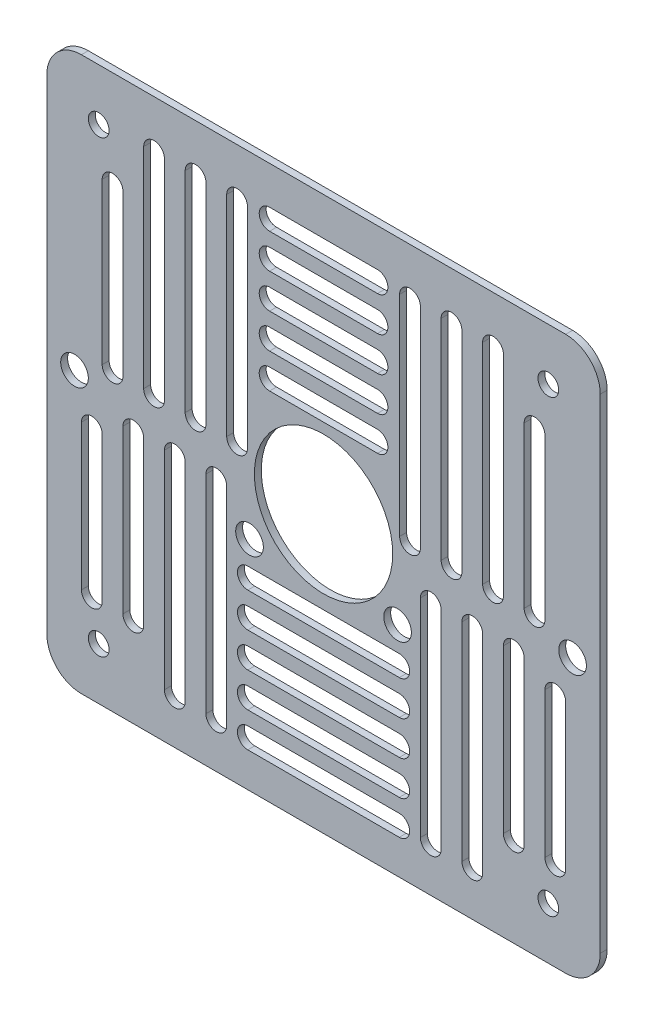
SolidWorks part; units mm, degrees
material "Fibra de vidrio-A"
ref_plane "Alzado" through (0, 0, 0) normal (0, 0, 1) x (1, 0, 0)
ref_plane "Planta" through (0, 0, 0) normal (0, 1, 0) x (1, 0, 0)
ref_plane "Vista lateral" through (0, 0, 0) normal (1, 0, 0) x (0, 0, -1)
sketch "Croquis1" plane through (0, 0, 0) normal (0, 0, 1) x (1, 0, 0)
  line L1 (-35, -40) -> (35, -40)
  line L2 (-40, -35) -> (-40, 35)
  line L3 (-35, 40) -> (35, 40)
  line L4 (40, -35) -> (40, 35)
  line L5 (-40, -40) -> (40, 40) construction
  line L6 (-40, 40) -> (40, -40) construction
  circle A0 centre (0, 0) radius 10
  arc A1 (35, -40) -> (40, -35) centre (35, -35) ccw
  arc A2 (-35, -40) -> (-40, -35) centre (-35, -35) cw
  arc A3 (35, 40) -> (40, 35) centre (35, 35) cw
  arc A4 (-40, 35) -> (-35, 40) centre (-35, 35) cw
  point P0 (0, 0)
  dimension "D2" = 20
  dimension "D3" = 5
  dimension "D1" = 80
extrude "Saliente-Extruir1" add sketch "Croquis1" against normal blind 1
sketch "Croquis2" plane through (0, 0, 0) normal (0, 0, 1) x (1, 0, 0)
  line L0 (-40, 0) -> (40, 0) construction
  line L1 (40, -35) -> (40, 35) construction
  line L2 (0, 0) -> (0, 10) construction
  line L3 (-35, -40) -> (35, -40) construction
  circle A0 centre (36, 0) radius 2
  circle A1 centre (0, 0) radius 10 construction
  circle A2 centre (-36, 0) radius 2
  circle A3 centre (32.5, -32.5) radius 1.5
  circle A4 centre (32.5, 32.5) radius 1.5
  circle A5 centre (-32.5, -32.5) radius 1.5
  circle A6 centre (-32.5, 32.5) radius 1.5
  circle A7 centre (10.7, -8.5) radius 2
  circle A8 centre (-10.7, -8.5) radius 2
  point P7 (0, 0)
  dimension "D1" = 4
  dimension "D2" = 4
  dimension "D3" = 3
  dimension "D4" = 7.5
  dimension "D6" = 4
  dimension "D7" = 31.5
  dimension "D8" = 29.3
  dimension "D5" = 7.5
extrude "Cortar-Extruir1" cut sketch "Croquis2" against normal blind 1
sketch "Croquis3" plane through (0, 0, 0) normal (0, 0, 1) x (1, 0, 0)
  line L0 (0, 0) -> (0, 40) construction
  line L1 (35, 40) -> (-35, 40) construction
  line L2 (-7.8, 33) -> (7.8, 33) construction
  line L3 (-7.8, 26.5) -> (7.8, 26.5)
  line L4 (-7.8, 34.5) -> (7.8, 34.5)
  line L5 (-7.8, 31.5) -> (7.8, 31.5)
  line L6 (-7.8, 29.5) -> (7.8, 29.5)
  line L7 (-7.8, 28) -> (7.8, 28) construction
  line L8 (-7.8, 21.5) -> (7.8, 21.5)
  line L9 (-7.8, 24.5) -> (7.8, 24.5)
  line L10 (-7.8, 23) -> (7.8, 23) construction
  line L11 (-7.8, 16.5) -> (7.8, 16.5)
  line L12 (-7.8, 19.5) -> (7.8, 19.5)
  line L13 (-7.8, 18) -> (7.8, 18) construction
  line L14 (-7.8, 11.5) -> (7.8, 11.5)
  line L15 (-7.8, 14.5) -> (7.8, 14.5)
  line L16 (-7.8, 13) -> (7.8, 13) construction
  line L17 (0, 0) -> (0, -40) construction
  line L18 (-35, -40) -> (35, -40) construction
  line L19 (-10.95, -33.5) -> (10.95, -33.5) construction
  line L20 (-10.95, -30) -> (10.95, -30)
  line L21 (-10.95, -32) -> (10.95, -32)
  line L22 (-10.95, -35) -> (10.95, -35)
  line L23 (-10.95, -27) -> (10.95, -27)
  line L24 (-10.95, -28.5) -> (10.95, -28.5) construction
  line L25 (-10.95, -25) -> (10.95, -25)
  line L26 (-10.95, -22) -> (10.95, -22)
  line L27 (-10.95, -23.5) -> (10.95, -23.5) construction
  line L28 (-10.95, -20) -> (10.95, -20)
  line L29 (-10.95, -17) -> (10.95, -17)
  line L30 (-10.95, -18.5) -> (10.95, -18.5) construction
  line L31 (-10.95, -15) -> (10.95, -15)
  line L32 (-10.95, -12) -> (10.95, -12)
  line L33 (-10.95, -13.5) -> (10.95, -13.5) construction
  arc A0 (-7.8, 34.5) -> (-7.8, 31.5) centre (-7.8, 33) ccw
  arc A1 (7.8, 31.5) -> (7.8, 34.5) centre (7.8, 33) ccw
  arc A2 (-7.8, 29.5) -> (-7.8, 26.5) centre (-7.8, 28) ccw
  arc A3 (7.8, 26.5) -> (7.8, 29.5) centre (7.8, 28) ccw
  arc A4 (-7.8, 24.5) -> (-7.8, 21.5) centre (-7.8, 23) ccw
  arc A5 (7.8, 21.5) -> (7.8, 24.5) centre (7.8, 23) ccw
  arc A6 (-7.8, 19.5) -> (-7.8, 16.5) centre (-7.8, 18) ccw
  arc A7 (7.8, 16.5) -> (7.8, 19.5) centre (7.8, 18) ccw
  arc A8 (-7.8, 14.5) -> (-7.8, 11.5) centre (-7.8, 13) ccw
  arc A9 (7.8, 11.5) -> (7.8, 14.5) centre (7.8, 13) ccw
  arc A10 (-10.95, -32) -> (-10.95, -35) centre (-10.95, -33.5) ccw
  arc A11 (10.95, -35) -> (10.95, -32) centre (10.95, -33.5) ccw
  arc A12 (-10.95, -27) -> (-10.95, -30) centre (-10.95, -28.5) ccw
  arc A13 (10.95, -30) -> (10.95, -27) centre (10.95, -28.5) ccw
  arc A14 (-10.95, -22) -> (-10.95, -25) centre (-10.95, -23.5) ccw
  arc A15 (10.95, -25) -> (10.95, -22) centre (10.95, -23.5) ccw
  arc A16 (-10.95, -17) -> (-10.95, -20) centre (-10.95, -18.5) ccw
  arc A17 (10.95, -20) -> (10.95, -17) centre (10.95, -18.5) ccw
  arc A18 (-10.95, -12) -> (-10.95, -15) centre (-10.95, -13.5) ccw
  arc A19 (10.95, -15) -> (10.95, -12) centre (10.95, -13.5) ccw
  point P9 (0, 33)
  point P15 (0, 28)
  point P22 (0, 23)
  point P29 (0, 18)
  point P36 (0, 13)
  point P47 (0, -33.5)
  point P54 (0, -28.5)
  point P61 (0, -23.5)
  point P68 (0, -18.5)
  point P75 (0, -13.5)
  dimension "D3" = 5
  dimension "D1" = 5.5
  dimension "D2" = 3
  dimension "D4" = 3
  dimension "D5" = 5
  dimension "D7" = 21.9
  dimension "D8" = 15.6
  dimension "D6" = 5
extrude "Cortar-Extruir2" cut sketch "Croquis3" against normal blind 1
sketch "Croquis4" plane through (0, 0, 0) normal (0, 0, 1) x (1, 0, 0)
  line L0 (12.5, 2.7) -> (12.5, 33) construction
  line L1 (40, -35) -> (40, 35) construction
  line L2 (11, 2.7) -> (11, 33)
  line L3 (14, 2.7) -> (14, 33)
  line L4 (3.8705, 34.5) -> (26.7887, 34.5) construction
  line L5 (18.5, 2.7) -> (18.5, 33) construction
  line L6 (7.8, 34.5) -> (-7.8, 34.5) construction
  line L7 (17, 2.7) -> (17, 33)
  line L8 (20, 2.7) -> (20, 33)
  line L9 (24.5, 2.7) -> (24.5, 33) construction
  line L10 (23, 2.7) -> (23, 33)
  line L11 (26, 2.7) -> (26, 33)
  line L12 (12.5, 1.2) -> (40, 1.2) construction
  line L13 (30.5, 25.9) -> (30.5, 2.7) construction
  line L14 (0, 0) -> (0, 40) construction
  line L15 (32, 25.9) -> (32, 2.7)
  line L16 (29, 25.9) -> (29, 2.7)
  line L17 (35, 40) -> (-35, 40) construction
  line L18 (-12.5, 2.7) -> (-12.5, 33) construction
  line L19 (-11, 2.7) -> (-11, 33)
  line L20 (-14, 2.7) -> (-14, 33)
  line L21 (-18.5, 2.7) -> (-18.5, 33) construction
  line L22 (-17, 2.7) -> (-17, 33)
  line L23 (-20, 2.7) -> (-20, 33)
  line L24 (-24.5, 2.7) -> (-24.5, 33) construction
  line L25 (-23, 2.7) -> (-23, 33)
  line L26 (-26, 2.7) -> (-26, 33)
  line L27 (-30.5, 25.9) -> (-30.5, 2.7) construction
  line L28 (-32, 25.9) -> (-32, 2.7)
  line L29 (-29, 25.9) -> (-29, 2.7)
  arc A0 (11, 2.7) -> (14, 2.7) centre (12.5, 2.7) ccw
  arc A1 (14, 33) -> (11, 33) centre (12.5, 33) ccw
  arc A2 (17, 2.7) -> (20, 2.7) centre (18.5, 2.7) ccw
  arc A3 (20, 33) -> (17, 33) centre (18.5, 33) ccw
  arc A4 (23, 2.7) -> (26, 2.7) centre (24.5, 2.7) ccw
  arc A5 (26, 33) -> (23, 33) centre (24.5, 33) ccw
  arc A6 (32, 25.9) -> (29, 25.9) centre (30.5, 25.9) ccw
  arc A7 (29, 2.7) -> (32, 2.7) centre (30.5, 2.7) ccw
  arc A8 (-11, 2.7) -> (-14, 2.7) centre (-12.5, 2.7) cw
  arc A9 (-14, 33) -> (-11, 33) centre (-12.5, 33) cw
  arc A10 (-17, 2.7) -> (-20, 2.7) centre (-18.5, 2.7) cw
  arc A11 (-20, 33) -> (-17, 33) centre (-18.5, 33) cw
  arc A12 (-23, 2.7) -> (-26, 2.7) centre (-24.5, 2.7) cw
  arc A13 (-26, 33) -> (-23, 33) centre (-24.5, 33) cw
  arc A14 (-32, 25.9) -> (-29, 25.9) centre (-30.5, 25.9) cw
  arc A15 (-29, 2.7) -> (-32, 2.7) centre (-30.5, 2.7) cw
  point P4 (12.5, 17.85)
  point P17 (18.5, 17.85)
  point P24 (24.5, 17.85)
  point P33 (30.5, 14.3)
  point P43 (-12.5, 17.85)
  point P50 (-18.5, 17.85)
  point P57 (-24.5, 17.85)
  point P64 (-30.5, 14.3)
  dimension "D1" = 26
  dimension "D2" = 3
  dimension "D3" = 3
  dimension "D4" = 26.2
  dimension "D5" = 3
extrude "Cortar-Extruir3" cut sketch "Croquis4" against normal blind 1
sketch "Croquis5" plane through (0, 0, 0) normal (0, 0, 1) x (1, 0, 0)
  line L0 (14, 17.85) -> (17, 17.85) construction
  line L1 (14, 2.7) -> (14, 33) construction
  line L2 (17, 33) -> (17, 2.7) construction
  line L3 (15.5, 17.85) -> (15.5, -40) construction
  line L4 (-35, -40) -> (35, -40) construction
  line L5 (15.5, -3.5) -> (15.5, -33.5) construction
  line L6 (17, -3.5) -> (17, -33.5)
  line L7 (14, -3.5) -> (14, -33.5)
  line L8 (10.95, -35) -> (40, -35) construction
  line L9 (20, -3.5) -> (20, -33.5)
  line L10 (23, -3.5) -> (23, -33.5)
  line L11 (21.5, -3.5) -> (21.5, -33.5) construction
  line L12 (26, 17.85) -> (29, 17.85) construction
  line L13 (26, 2.7) -> (26, 33) construction
  line L14 (29, 25.9) -> (29, 2.7) construction
  line L15 (27.5, 17.85) -> (27.5, -35) construction
  line L16 (27.5, -3.5) -> (27.5, -27) construction
  line L17 (29, -3.5) -> (29, -27)
  line L18 (26, -3.5) -> (26, -27)
  line L19 (27.5, -28.5) -> (40, -28.5) construction
  line L21 (33.5, -27) -> (33.5, -6) construction
  line L22 (32, -27) -> (32, -6)
  line L23 (35, -27) -> (35, -6)
  line L24 (40, -35) -> (40, 35) construction
  line L25 (0, 0) -> (0, -40) construction
  line L26 (-15.5, -3.5) -> (-15.5, -33.5) construction
  line L27 (-17, -3.5) -> (-17, -33.5)
  line L28 (-14, -3.5) -> (-14, -33.5)
  line L29 (-21.5, -3.5) -> (-21.5, -33.5) construction
  line L30 (-23, -3.5) -> (-23, -33.5)
  line L31 (-20, -3.5) -> (-20, -33.5)
  line L32 (-27.5, -3.5) -> (-27.5, -27) construction
  line L33 (-29, -3.5) -> (-29, -27)
  line L34 (-26, -3.5) -> (-26, -27)
  line L35 (-33.5, -27) -> (-33.5, -6) construction
  line L36 (-32, -27) -> (-32, -6)
  line L37 (-35, -27) -> (-35, -6)
  arc A0 (17, -3.5) -> (14, -3.5) centre (15.5, -3.5) ccw
  arc A1 (14, -33.5) -> (17, -33.5) centre (15.5, -33.5) ccw
  arc A2 (23, -3.5) -> (20, -3.5) centre (21.5, -3.5) ccw
  arc A3 (20, -33.5) -> (23, -33.5) centre (21.5, -33.5) ccw
  arc A4 (29, -3.5) -> (26, -3.5) centre (27.5, -3.5) ccw
  arc A5 (26, -27) -> (29, -27) centre (27.5, -27) ccw
  arc A6 (32, -27) -> (35, -27) centre (33.5, -27) ccw
  arc A7 (35, -6) -> (32, -6) centre (33.5, -6) ccw
  arc A8 (-17, -3.5) -> (-14, -3.5) centre (-15.5, -3.5) cw
  arc A9 (-14, -33.5) -> (-17, -33.5) centre (-15.5, -33.5) cw
  arc A10 (-23, -3.5) -> (-20, -3.5) centre (-21.5, -3.5) cw
  arc A11 (-20, -33.5) -> (-23, -33.5) centre (-21.5, -33.5) cw
  arc A12 (-29, -3.5) -> (-26, -3.5) centre (-27.5, -3.5) cw
  arc A13 (-26, -27) -> (-29, -27) centre (-27.5, -27) cw
  arc A14 (-32, -27) -> (-35, -27) centre (-33.5, -27) cw
  arc A15 (-35, -6) -> (-32, -6) centre (-33.5, -6) cw
  point P12 (15.5, -18.5)
  point P25 (21.5, -18.5)
  point P38 (27.5, -15.25)
  point P49 (33.5, -16.5)
  point P59 (-15.5, -18.5)
  point P66 (-21.5, -18.5)
  point P73 (-27.5, -15.25)
  point P80 (-33.5, -16.5)
  dimension "D1" = 3
  dimension "D2" = 33
  dimension "D3" = 2
  dimension "D4" = 3
  dimension "D5" = 26.5
  dimension "D6" = 3
  dimension "D7" = 24
  dimension "D8" = 3
extrude "Cortar-Extruir4" cut sketch "Croquis5" against normal blind 1
